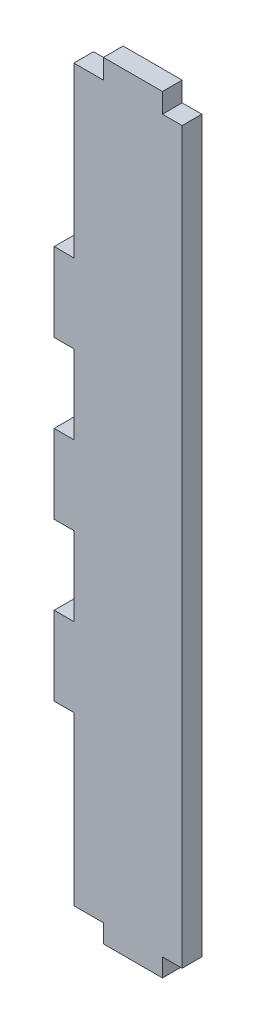
SolidWorks part; units mm, degrees
ref_plane "Front Plane" through (0, 0, 0) normal (0, 0, 1) x (1, 0, 0)
ref_plane "Top Plane" through (0, 0, 0) normal (0, 1, 0) x (1, 0, 0)
ref_plane "Right Plane" through (0, 0, 0) normal (1, 0, 0) x (0, 0, -1)
sketch "Sketch1" plane through (0, 0, 0) normal (0, 0, 1) x (1, 0, 0)
  line L0 (47.5, 185.3585) -> (52.5, 185.3585)
  line L1 (25, 185.3585) -> (32.5, 185.3585)
  line L6 (47.5, 185.3585) -> (47.5, 190.3585)
  line L7 (47.5, 190.3585) -> (32.5, 190.3585)
  line L8 (32.5, 185.3585) -> (32.5, 190.3585)
  line L9 (27.0339, 190.3585) -> (13.4221, 190.3585) construction
  line L10 (25, 185.3585) -> (25, 142.5)
  line L11 (55, 102.5) -> (29.9104, 102.5) construction
  line L12 (1040, 92.5) -> (40, 92.5) construction
  line L13 (25, 102.5) -> (-997.5, 102.5) construction
  line L23 (25, 102.5) -> (20, 102.5)
  line L28 (25, 82.5) -> (20, 82.5)
  line L29 (20, 102.5) -> (20, 82.5)
  line L36 (40, 190.3585) -> (40, 122.0807) construction
  line L37 (40, -4.6415) -> (47.5, -4.6415)
  line L38 (47.5, -4.6415) -> (47.5, 0)
  line L39 (47.5, 0) -> (52.5, 0)
  line L40 (40, -4.6415) -> (32.5, -4.6415)
  line L41 (32.5, -4.6415) -> (32.5, 0)
  line L42 (32.5, 0) -> (25, 0)
  line L44 (52.5, 0) -> (52.5, 185.3585)
  line L48 (25, 62.5) -> (20, 62.5)
  line L49 (25, 82.5) -> (25, 62.5)
  line L50 (20.0896, 102.5) -> (20, 102.5) construction
  line L51 (20, 62.5) -> (20, 42.5)
  line L52 (25, 42.5) -> (20, 42.5)
  line L53 (25, 42.5) -> (25, 0)
  line L54 (25, 142.5) -> (20, 142.5)
  line L55 (20, 122.5) -> (20, 142.5)
  line L56 (25, 122.5) -> (20, 122.5)
  line L57 (25, 122.5) -> (25, 102.5)
  point P5 (31.1676, 178.2486)
  point P9 (20, 92.5)
  dimension "D1" = 15
  dimension "D2" = 5
  dimension "D3" = 15
  dimension "D4" = 20
  dimension "D5" = 5
  dimension "D8" = 7.5
  dimension "D9" = 5
  dimension "D10" = 7.5
  dimension "D6" = 2
extrude "Boss-Extrude1" add sketch "Sketch1" against normal blind 5
